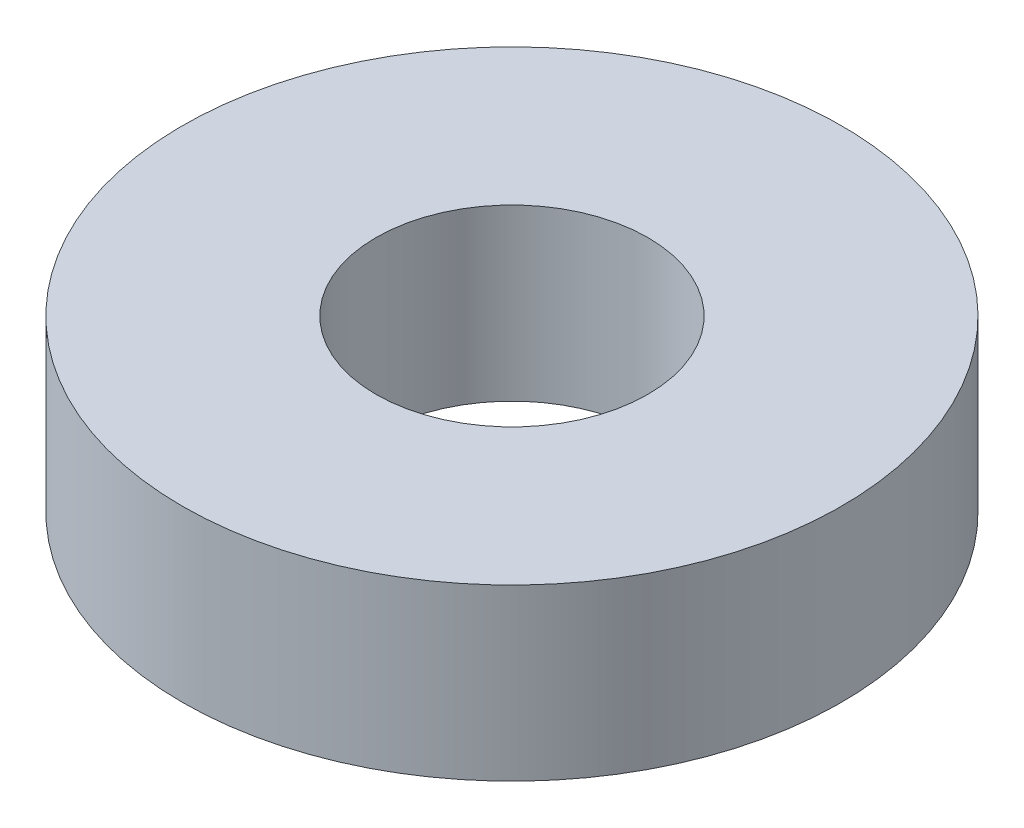
SolidWorks part; units mm, degrees
material "6061 합금"
ref_plane "정면" through (0, 0, 0) normal (0, 0, 1) x (1, 0, 0)
ref_plane "윗면" through (0, 0, 0) normal (0, 1, 0) x (1, 0, 0)
ref_plane "우측면" through (0, 0, 0) normal (1, 0, 0) x (0, 0, -1)
sketch "스케치1" plane through (0, 0, 0) normal (0, 1, 0) x (1, 0, 0)
  circle A0 centre (0, 0) radius 4
  circle A1 centre (0, 0) radius 9.7
  dimension "D1" = 19.4
  dimension "D2" = 8
extrude "보스-돌출1" add sketch "스케치1" along normal blind 5
